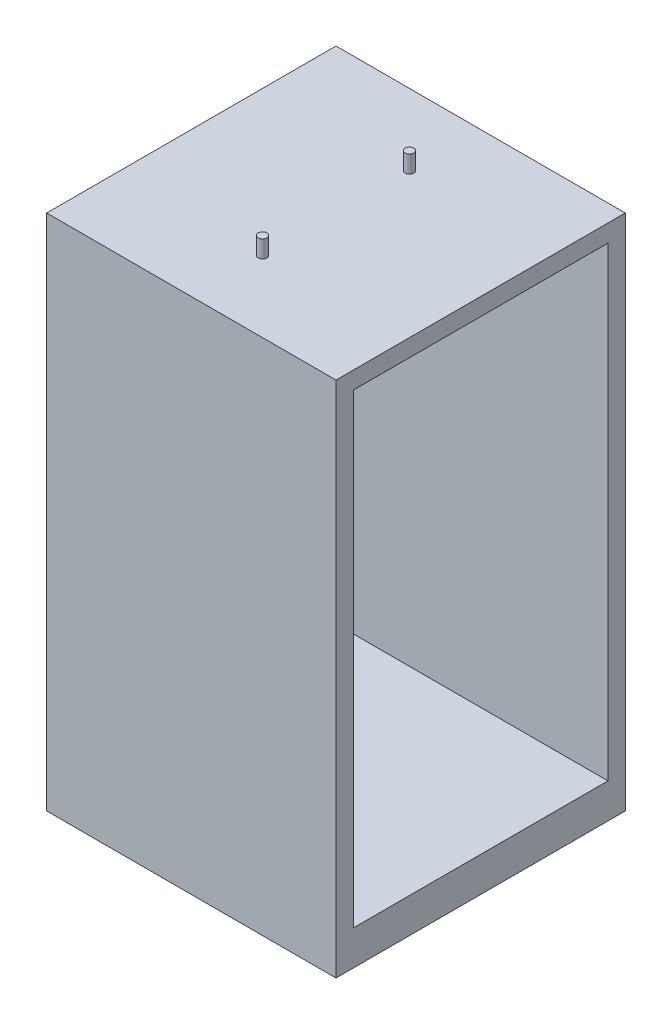
SolidWorks part; units mm, degrees
ref_plane "Front Plane" through (0, 0, 0) normal (0, 0, 1) x (1, 0, 0)
ref_plane "Top Plane" through (0, 0, 0) normal (0, 1, 0) x (1, 0, 0)
ref_plane "Right Plane" through (0, 0, 0) normal (1, 0, 0) x (0, 0, -1)
sketch "Sketch1" plane through (0, 0, 0) normal (0, 1, 0) x (1, 0, 0)
  line L0 (-28.1653, 15.3933) -> (21.8347, 15.3933)
  line L1 (21.8347, 15.3933) -> (21.8347, -34.6067)
  line L2 (21.8347, -34.6067) -> (-28.1653, -34.6067)
  line L5 (-28.1653, -34.6067) -> (-28.1653, 15.3933)
extrude "Boss-Extrude2" add sketch "Sketch1" along normal blind 89.5
sketch "Sketch4" plane through (21.8347, 0, 0) normal (1, 0, 0) x (0, 0, -1)
  line L3 (-31.6067, 86.5) -> (12.3933, 86.5)
  line L7 (-31.6067, 6) -> (-31.6067, 86.5)
  line L8 (-31.6067, 6) -> (12.3933, 6)
  line L9 (12.3933, 6) -> (12.3933, 86.5)
extrude "Cut-Extrude1" cut sketch "Sketch4" against normal blind 89.5
sketch "Sketch5" plane through (0, 0, 0) normal (0, -1, 0) x (-1, 0, 0)
  circle A0 centre (3.1653, -22.3067) radius 0.75
  circle A1 centre (3.1653, 3.0933) radius 0.75
extrude "Cut-Extrude2" cut sketch "Sketch5" against normal blind 3 contours A0 | A1
sketch "Sketch6" plane through (0, 89.5, 0) normal (0, 1, 0) x (1, 0, 0)
  circle A0 centre (-3.1653, 3.0933) radius 0.75
  circle A1 centre (-3.1653, -22.3067) radius 0.75
  point P4 (0, 0)
extrude "Boss-Extrude4" add sketch "Sketch6" along normal blind 3 contours A1 | A0
